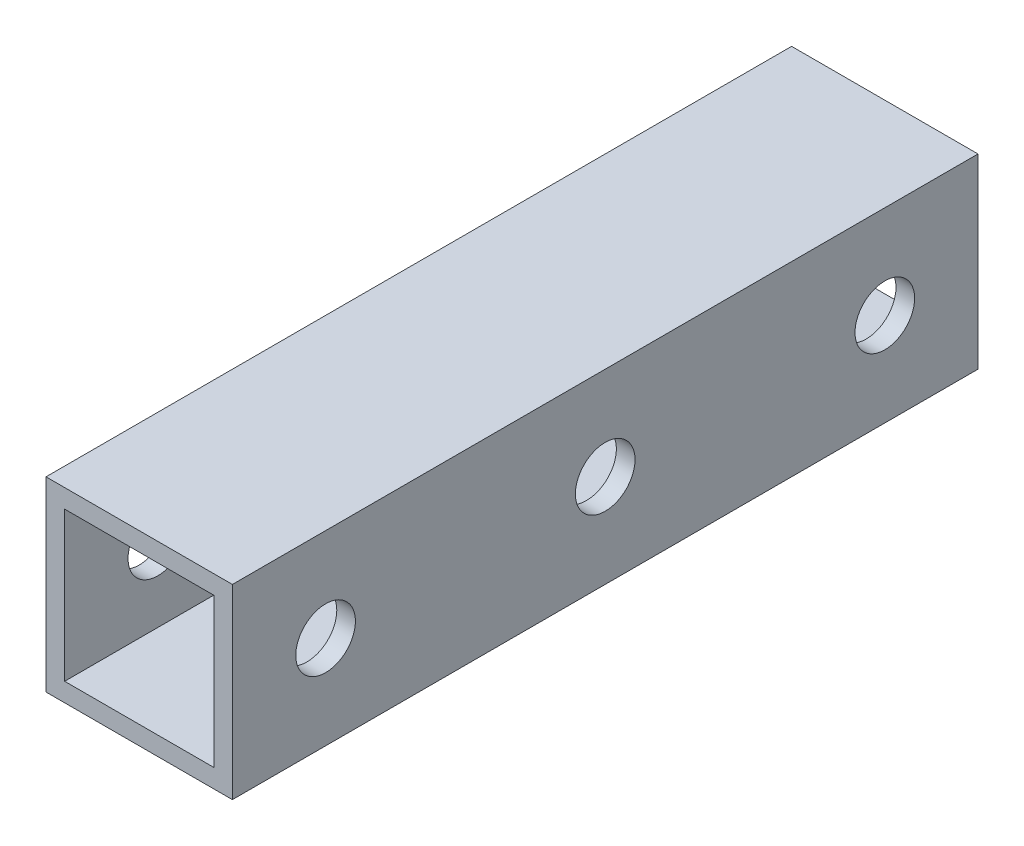
SolidWorks part; units mm, degrees
material "1060 合金"
ref_plane "正面" through (0, 0, 0) normal (0, 0, 1) x (1, 0, 0)
ref_plane "平面" through (0, 0, 0) normal (0, 1, 0) x (1, 0, 0)
ref_plane "右側面" through (0, 0, 0) normal (1, 0, 0) x (0, 0, -1)
sketch "ｽｹｯﾁ1" plane through (0, 0, 0) normal (0, 0, 1) x (1, 0, 0)
  line L1 (-5, -5) -> (5, -5)
  line L2 (-5, -5) -> (-5, 5)
  line L3 (-5, 5) -> (5, 5)
  line L4 (5, -5) -> (5, 5)
  line L5 (-5, -5) -> (5, 5) construction
  line L6 (-5, 5) -> (5, -5) construction
  point P0 (0, 0)
  dimension "D1" = 10
extrude "押し出し-薄板1" add sketch "ｽｹｯﾁ1" along normal blind 40 thin thin type one direction reverse wall 1
sketch "ｽｹｯﾁ3" plane through (5, 0, 0) normal (1, 0, 0) x (0, 0, -1)
  line L0 (-40, 0) -> (0, 0) construction
  line L1 (-40, -5) -> (-40, 5) construction
  line L2 (0, -5) -> (0, 5) construction
  circle A0 centre (-35, 0) radius 1.6
  circle A1 centre (-20, 0) radius 1.6
  circle A2 centre (-5, 0) radius 1.6
  dimension "D1" = 5
  dimension "D2" = 3.2
  dimension "D3" = 5
extrude "ｶｯﾄ - 押し出し2" cut sketch "ｽｹｯﾁ3" against normal through all
